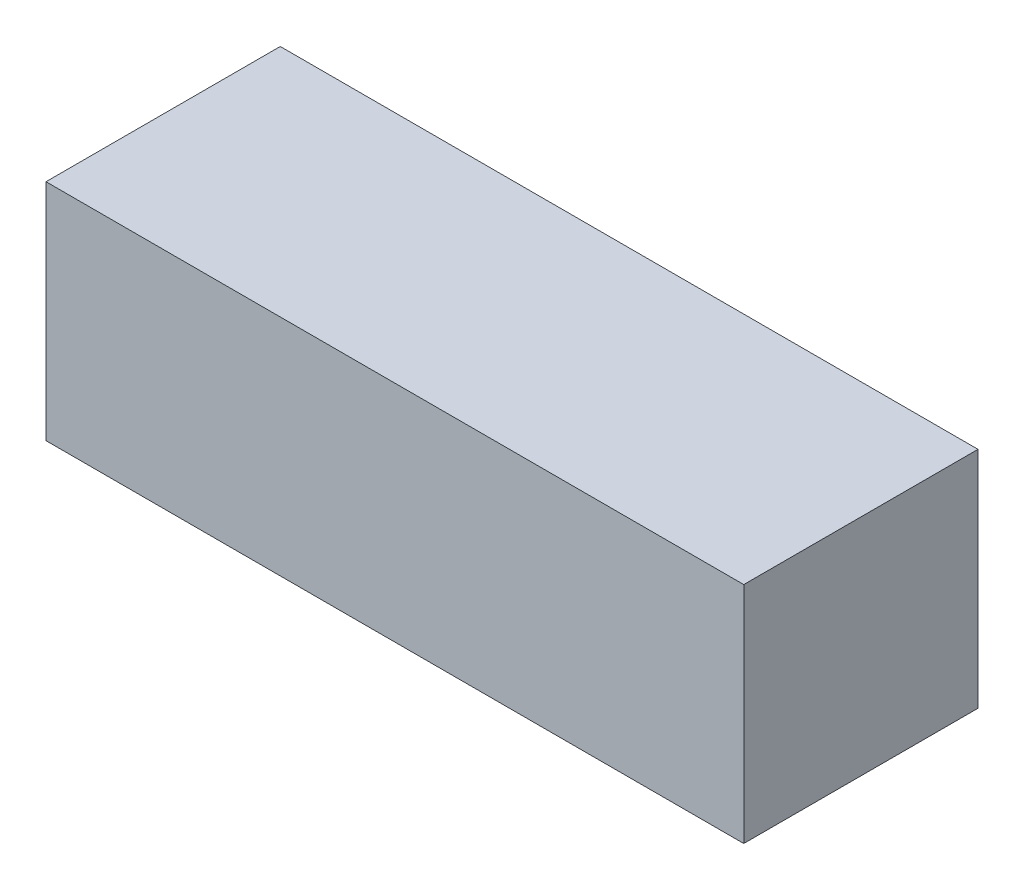
SolidWorks part; units mm, degrees
ref_plane "Front Plane" through (0, 0, 0) normal (0, 0, 1) x (1, 0, 0)
ref_plane "Top Plane" through (0, 0, 0) normal (0, 1, 0) x (1, 0, 0)
ref_plane "Right Plane" through (0, 0, 0) normal (1, 0, 0) x (0, 0, -1)
sketch "Sketch1" plane through (0, 0, 0) normal (0, 0, 1) x (1, 0, 0)
  line L1 (0, 0) -> (140, 0)
  line L2 (0, 0) -> (0, 45)
  line L3 (0, 45) -> (140, 45)
  line L4 (140, 0) -> (140, 45)
  dimension "D1" = 140
  dimension "D2" = 45
extrude "Boss-Extrude1" add sketch "Sketch1" along normal blind 47
